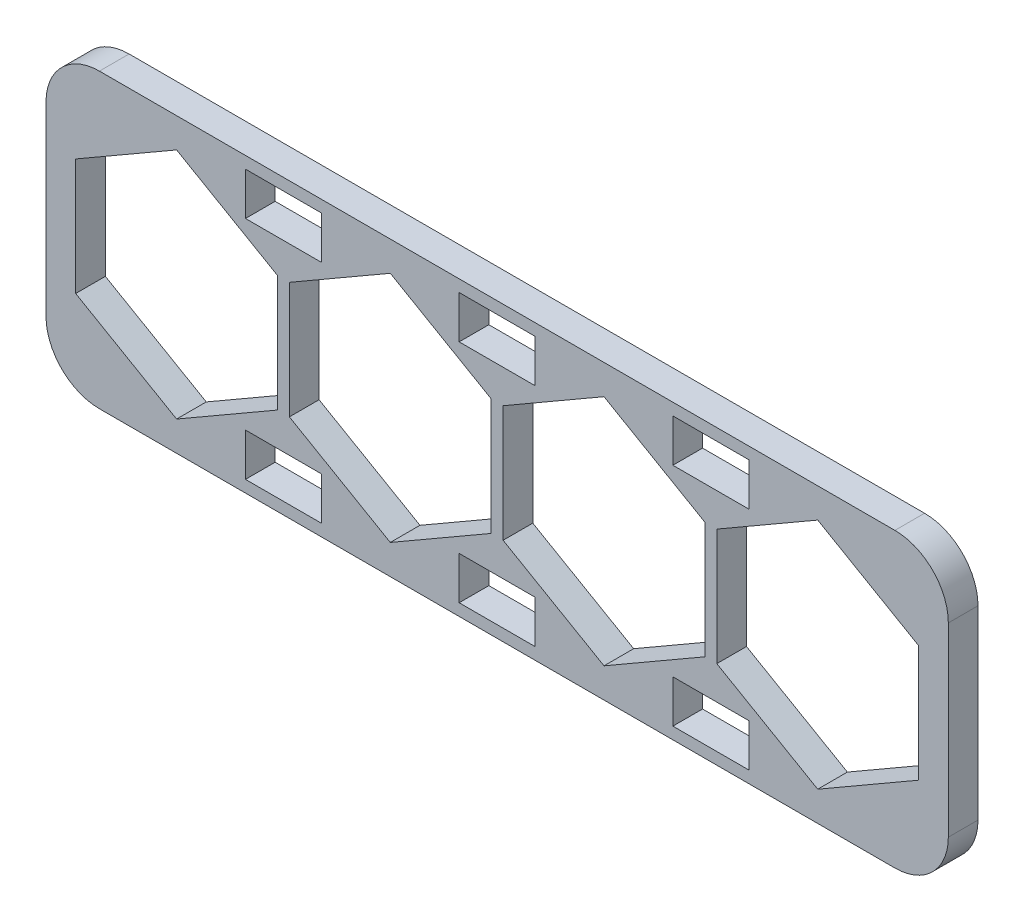
SolidWorks part; units mm, degrees
ref_plane "Front Plane" through (0, 0, 0) normal (0, 0, 1) x (1, 0, 0)
ref_plane "Top Plane" through (0, 0, 0) normal (0, 1, 0) x (1, 0, 0)
ref_plane "Right Plane" through (0, 0, 0) normal (1, 0, 0) x (0, 0, -1)
sketch "Sketch1" plane through (0, 0, 0) normal (0, 0, 1) x (1, 0, 0)
  line L0 (12.065, -6.2325) -> (22.86, -12.465)
  line L5 (34.925, -6.2325) -> (45.72, -12.465)
  line L7 (-10.795, -6.2325) -> (0, -12.465)
  line L8 (0, -12.465) -> (10.795, -6.2325)
  line L9 (10.795, -6.2325) -> (10.795, 6.2325)
  line L10 (10.795, 6.2325) -> (0, 12.465)
  line L11 (0, 12.465) -> (-10.795, 6.2325)
  line L12 (-10.795, 6.2325) -> (-10.795, -6.2325)
  line L13 (22.86, -12.465) -> (33.655, -6.2325)
  line L14 (33.655, -6.2325) -> (33.655, 6.2325)
  line L15 (33.655, 6.2325) -> (22.86, 12.465)
  line L16 (22.86, 12.465) -> (12.065, 6.2325)
  line L17 (12.065, 6.2325) -> (12.065, -6.2325)
  line L24 (0, 0) -> (0, 12.465) construction
  line L37 (45.72, -12.465) -> (56.515, -6.2325)
  line L38 (56.515, -6.2325) -> (56.515, 6.2325)
  line L39 (56.515, 6.2325) -> (45.72, 12.465)
  line L40 (45.72, 12.465) -> (34.925, 6.2325)
  line L41 (34.925, 6.2325) -> (34.925, -6.2325)
  line L42 (57.785, -6.2325) -> (68.58, -12.465)
  line L43 (68.58, -12.465) -> (79.375, -6.2325)
  line L44 (79.375, -6.2325) -> (79.375, 6.2325)
  line L45 (79.375, 6.2325) -> (68.58, 12.465)
  line L46 (68.58, 12.465) -> (57.785, 6.2325)
  line L47 (57.785, 6.2325) -> (57.785, -6.2325)
  line L49 (-8.255, 12.465) -> (76.835, 12.465)
  line L50 (-10.795, 9.925) -> (-10.795, -9.925)
  line L51 (-8.255, -12.465) -> (76.835, -12.465)
  line L52 (79.375, 9.925) -> (79.375, -9.925)
  line L53 (-8.255, 15.64) -> (76.835, 15.64)
  line L54 (82.55, 9.925) -> (82.55, -9.925)
  line L55 (-8.255, -15.64) -> (76.835, -15.64)
  line L56 (-13.97, 9.925) -> (-13.97, -9.925)
  line L57 (10.795, 6.2325) -> (12.065, 6.2325) construction
  line L59 (11.43, 6.2325) -> (11.43, 15.64) construction
  line L60 (30.226, 14.37) -> (30.226, 9.798)
  line L62 (7.366, 14.37) -> (15.494, 14.37)
  line L63 (7.366, 14.37) -> (7.366, 9.798)
  line L64 (7.366, 9.798) -> (15.494, 9.798)
  line L65 (15.494, 14.37) -> (15.494, 9.798)
  line L69 (0, 0) -> (-13.97, 0) construction
  line L110 (30.226, 14.37) -> (38.354, 14.37)
  line L114 (7.366, 14.37) -> (7.366, 9.798)
  line L115 (38.354, 14.37) -> (38.354, 9.798)
  line L116 (30.226, 9.798) -> (38.354, 9.798)
  line L117 (53.086, 14.37) -> (53.086, 9.798)
  line L118 (53.086, 14.37) -> (61.214, 14.37)
  line L119 (61.214, 14.37) -> (61.214, 9.798)
  line L120 (53.086, 9.798) -> (61.214, 9.798)
  line L121 (53.086, -14.37) -> (61.214, -14.37)
  line L122 (61.214, -14.37) -> (61.214, -9.798)
  line L123 (53.086, -9.798) -> (61.214, -9.798)
  line L124 (53.086, -14.37) -> (53.086, -9.798)
  line L125 (30.226, -14.37) -> (38.354, -14.37)
  line L126 (38.354, -14.37) -> (38.354, -9.798)
  line L127 (30.226, -9.798) -> (38.354, -9.798)
  line L128 (30.226, -14.37) -> (30.226, -9.798)
  line L129 (7.366, -9.798) -> (15.494, -9.798)
  line L130 (15.494, -14.37) -> (15.494, -9.798)
  line L131 (7.366, -14.37) -> (15.494, -14.37)
  line L132 (7.366, -14.37) -> (7.366, -9.798)
  circle A0 centre (0, 0) radius 7.5565
  circle A1 centre (0, 0) radius 10.795 construction
  circle A2 centre (22.86, 0) radius 7.5565
  circle A3 centre (22.86, 0) radius 10.795 construction
  circle A5 centre (45.72, 0) radius 7.5565
  arc A7 (-8.255, 12.465) -> (-10.795, 9.925) centre (-8.255, 9.925) ccw
  circle A10 centre (45.72, 0) radius 10.795 construction
  circle A11 centre (68.58, 0) radius 7.5565
  circle A12 centre (68.58, 0) radius 10.795 construction
  arc A13 (79.375, 9.925) -> (76.835, 12.465) centre (76.835, 9.925) ccw
  arc A14 (-10.795, -9.925) -> (-8.255, -12.465) centre (-8.255, -9.925) ccw
  arc A15 (79.375, -9.925) -> (76.835, -12.465) centre (76.835, -9.925) cw
  arc A16 (82.55, 9.925) -> (76.835, 15.64) centre (76.835, 9.925) ccw
  arc A17 (82.55, -9.925) -> (76.835, -15.64) centre (76.835, -9.925) cw
  arc A18 (-13.97, -9.925) -> (-8.255, -15.64) centre (-8.255, -9.925) ccw
  arc A19 (-8.255, 15.64) -> (-13.97, 9.925) centre (-8.255, 9.925) ccw
  point P0 (0, 0)
  point P3 (45.72, 0)
  point P8 (22.86, 0)
  point P9 (11.43, 14.37)
  point P36 (68.58, 0)
  point P57 (-45.72, 0)
  dimension "D1" = 15.113
  dimension "D8" = 3.175
  dimension "D5" = 2.54
  dimension "D6" = 2.54
  dimension "D7" = 2.54
  dimension "D2" = 21.59
  dimension "D4" = 22.86
  dimension "D9" = 24.93
  dimension "D10" = 1.27
  dimension "D11" = 8.128
  dimension "D12" = 3
  dimension "D13" = 4.572
  dimension "D14" = 22.86
  dimension "D3" = 4
extrude "Boss-Extrude1" add sketch "Sketch1" along normal blind 3.175
